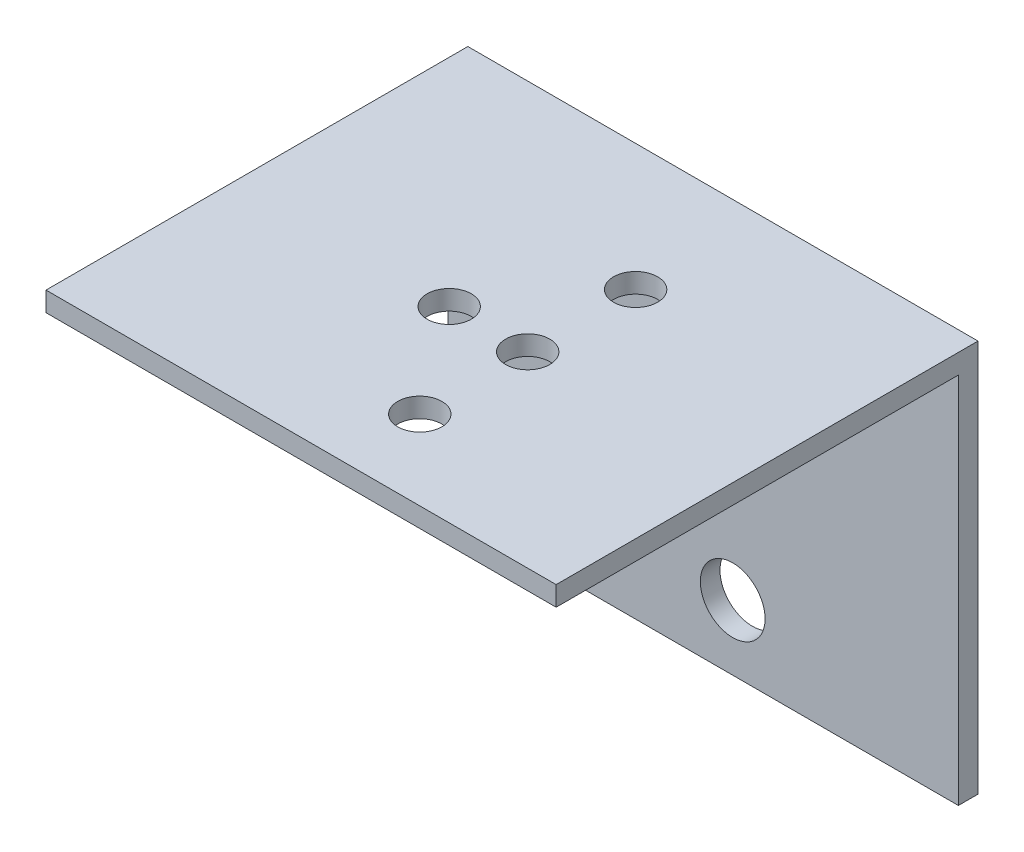
SolidWorks part; units mm, degrees
ref_plane "Plan de face" through (0, 0, 0) normal (0, 0, 1) x (1, 0, 0)
ref_plane "Plan de dessus" through (0, 0, 0) normal (0, 1, 0) x (1, 0, 0)
ref_plane "Plan de droite" through (0, 0, 0) normal (1, 0, 0) x (0, 0, -1)
sketch "Esquisse1" plane through (0, 0, 0) normal (0, 0, 1) x (1, 0, 0)
  line L1 (-26, -20) -> (26, -20)
  line L2 (-26, -20) -> (-26, 20)
  line L3 (-26, 20) -> (26, 20)
  line L4 (26, -20) -> (26, 20)
  line L5 (-26, -20) -> (26, 20) construction
  line L6 (-26, 20) -> (26, -20) construction
  point P0 (0, 0)
  dimension "D1" = 40
  dimension "D2" = 52
extrude "Boss.-Extru.1" add sketch "Esquisse1" along normal blind 43
sketch "Esquisse2" plane through (-26, 0, 0) normal (-1, 0, 0) x (0, 0, 1)
  line L8 (2, -18) -> (41, -18)
  line L9 (41, -18) -> (41, 18)
  line L10 (41, 18) -> (2, 18)
  line L11 (2, 18) -> (2, -18)
  line L12 (2, -18) -> (50.222, -18)
  line L13 (50.222, -18) -> (50.222, 18)
  line L14 (50.222, 18) -> (2, 18)
  line L15 (2, 18) -> (2, -18)
  dimension "D1" = 2
extrude "Enlèv. mat.-Extru.1" cut sketch "Esquisse2" against normal blind 50
sketch "Esquisse3" plane through (0, -20, 0) normal (0, -1, 0) x (1, 0, 0)
  line L8 (-24, 2) -> (24, 2)
  line L9 (24, 2) -> (24, 41)
  line L10 (24, 41) -> (-24, 41)
  line L11 (-24, 41) -> (-24, 2)
  line L12 (-34.6852, 2) -> (38.0009, 2)
  line L13 (38.0009, 2) -> (38.0009, 52.5344)
  line L14 (38.0009, 52.5344) -> (-34.6852, 52.5344)
  line L15 (-34.6852, 52.5344) -> (-34.6852, 2)
  dimension "D1" = 2
extrude "Enlèv. mat.-Extru.2" cut sketch "Esquisse3" against normal up to surface (38 mm away) up to face at (-1, 18, 22.5)
hole_wizard "Dégagement M61" positions "Esquisse5" profile "Esquisse4" hole size "M6" standard "JIS" end condition through all
sketch "Esquisse5" plane through (0, 0, 2) normal (0, 0, 1) x (1, 0, 0)
  point P0 (2.9974, 9.3205)
  point P2 (-16.4429, 9.3205)
  point P4 (-16.4429, -13.3785)
  point P6 (2.9974, -13.3785)
sketch "Esquisse4" plane through (2.9974, 9.3205, 2) normal (1, 0, 0) x (0, -1, 0)
  line L0 (0, 0) -> (0, 2)
  line L1 (0, 2) -> (3.3, 2)
  line L2 (3.3, 2) -> (3.3, 0)
  line L5 (3.3, 0) -> (0, 0)
  line L11 (0, -6.35) -> (0, 107.95) construction
  dimension "Diamètre du perçage jusqu'au prochain" = 6.6
  dimension "Profondeur du perçage jusqu'au prochain" = 2
hole_wizard "Dégagement M41" positions "Esquisse7" profile "Esquisse6" hole size "M4" standard "JIS" end condition through all
sketch "Esquisse7" plane through (0, 18, 0) normal (0, -1, 0) x (-1, 0, 0)
  point P0 (-4, -34.9)
  point P2 (-4, -23.9)
  point P4 (-4, -12.9)
  point P6 (4, -23.9)
sketch "Esquisse6" plane through (4, 18, 34.9) normal (1, 0, 0) x (0, 0, -1)
  line L0 (0, 0) -> (0, 2)
  line L1 (0, 2) -> (2.25, 2)
  line L2 (2.25, 2) -> (2.25, 0)
  line L5 (2.25, 0) -> (0, 0)
  line L11 (0, -6.35) -> (0, 107.95) construction
  dimension "Diamètre du perçage jusqu'au prochain" = 4.5
  dimension "Profondeur du perçage jusqu'au prochain" = 2
